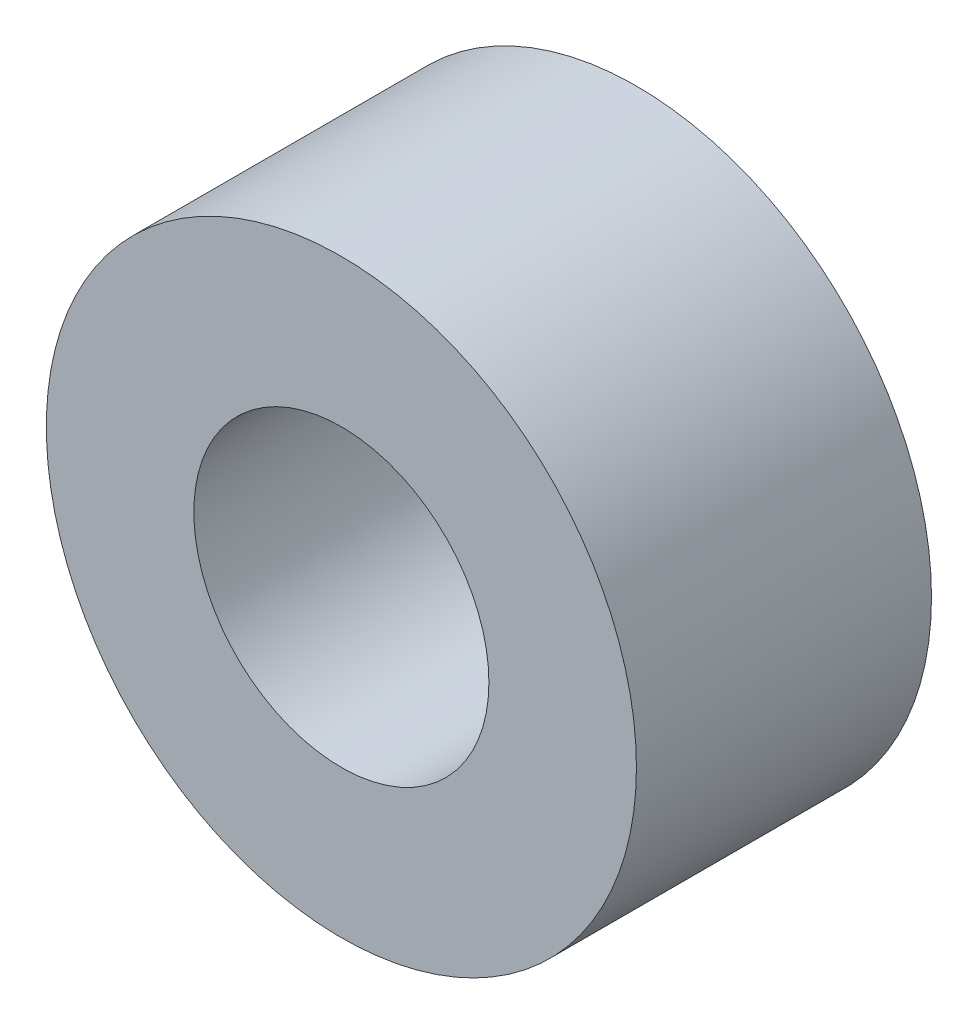
SolidWorks part; units mm, degrees
ref_plane "Plan1" through (0, 0, 0) normal (0, 0, 1) x (1, 0, 0)
ref_plane "Plan2" through (0, 0, 0) normal (0, 1, 0) x (1, 0, 0)
ref_plane "Plan3" through (0, 0, 0) normal (1, 0, 0) x (0, 0, -1)
sketch "Esquisse1" plane through (0, 0, 0) normal (0, 0, 1) x (1, 0, 0)
  circle A0 centre (0, 0) radius 10
extrude "Base-Extrusion" add sketch "Esquisse1" along normal blind 10
sketch "Esquisse2" plane through (0, 0, 10) normal (0, 0, 1) x (1, 0, 0)
  circle A0 centre (0, 0) radius 5
extrude "Enlèv. mat.-Extru.1" cut sketch "Esquisse2" against normal blind 10
